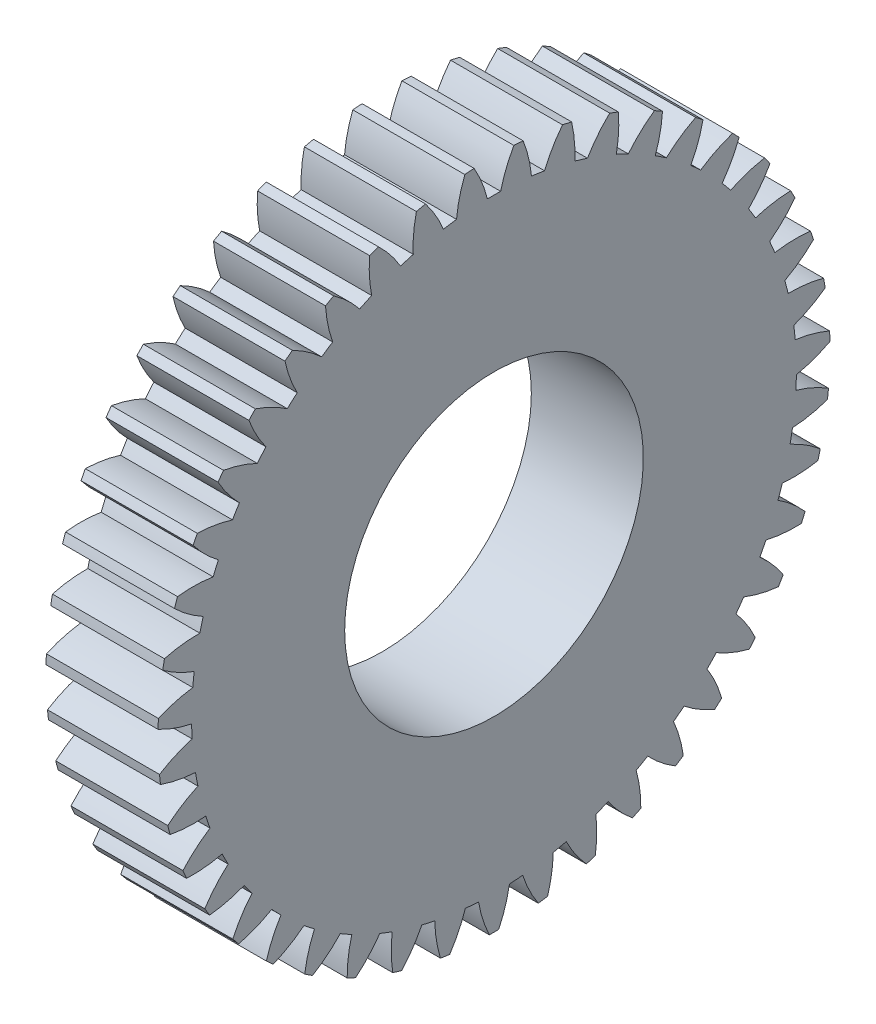
SolidWorks part; units mm, degrees
ref_plane "Plane1" through (0, 0, 0) normal (0, 0, 1) x (1, 0, 0)
ref_plane "Plane2" through (0, 0, 0) normal (0, 1, 0) x (1, 0, 0)
ref_plane "Plane3" through (0, 0, 0) normal (1, 0, 0) x (0, 0, -1)
sketch "HoldingSke" plane through (0, 0, 0) normal (0, 1, 0) x (1, 0, 0)
  line L0 (0, 0) -> (1.8284, -1.705)
  line L1 (-15, 0) -> (100, 0) construction
  line L2 (0, 0) -> (-2.1039, 2.3779)
  line L3 (0, 0) -> (-11.863, 4.5341)
  line L4 (0, 0) -> (6.316, 5.8897)
  line L5 (0, 0) -> (-46.8476, -17.4728)
  line L6 (0, 0) -> (-2.4869, -1.6779)
  line L7 (-2.1039, 2.3779) -> (8.6586, 51.2059)
  line L8 (-76.2, 54.61) -> (-74.8, 54.61)
  line L9 (-71.009, 38.7566) -> (-53.1078, 45.2721)
  line L10 (-76.2, 71.12) -> (104.1128, 71.12)
  line L11 (0, 0) -> (-3, 0)
  line L12 (-76.2, 101.6) -> (-76.185, 101.6)
  line L13 (24.9733, 27.94) -> (52.9518, 28.4284)
  line L14 (24.9733, 27.94) -> (24.9743, 27.94)
  line L15 (24.9733, 27.94) -> (100.4006, 29.5858)
  line L16 (-63.627, -0.4) -> (-12.827, -0.4)
  circle A0 centre (0, 0) radius 4
  circle A1 centre (0, 0) radius 8.099
  circle A2 centre (0, 0) radius 37.5
  circle A3 centre (0, 0) radius 4
  dimension "MHD" = 16.198
  dimension "Hub_dia" = 75
  dimension "Bore" = 8
  dimension "MBD" = 8
  dimension "Num_teeth" = 43
  dimension "Pitch" = 2.5
  dimension "Overall_len" = 50
  dimension "Show_teeth" = 43
  dimension "Thickness" = 3
  dimension "OAL" = 50.0001
  dimension "T_dim" = 1.4
  dimension "Ap" = 20
  dimension "H" = 19.05
  dimension "Pitch_radius" = 180.3128
  dimension "Width" = 3
  dimension "Backlash" = 0.015
  dimension "Addendum_fac" = 1
  dimension "Dedendum_fac" = 1.25
  dimension "Clearance_fac" = 0.25
  dimension "Dedendum_add" = 0.001
  dimension "Module" = 0.4
sketch "BasProSke" plane through (0, 0, 0) normal (0, 1, 0) x (1, 0, 0)
  line L0 (-10, 0) -> (60, 0) construction
  line L1 (0, 0) -> (0, 9)
  line L2 (0, 0) -> (3, 0)
  line L3 (3, 0) -> (3, 9)
  line L4 (3, 9) -> (0, 9)
  dimension "Thickness" = 3
  dimension "Diameter" = 18
revolve "Base-Revolve" add sketch "BasProSke" angle 360 about L0
sketch "TooCutSke" plane through (0, 0, 0) normal (1, 0, 0) x (0, 0, -1)
  line L1 (0, 0) -> (0, 107) construction
  line L2 (0, 0) -> (-0.3403, 8.5933) construction
  line L3 (0, 0) -> (-1.2548, 17.1445) construction
  line L4 (-0.3403, 8.5933) -> (-0.6274, 8.5723) construction
  arc A0 (0.1775, 8.0971) -> (-0.1775, 8.0971) centre (0, 0) ccw
  arc A1 (0.5465, 9.0088) -> (-0.5465, 9.0088) centre (0, 0) ccw
  circle A2 centre (0, 0) radius 8.6 construction
  circle A3 centre (0, 0) radius 8.0814 construction
  arc A4 (-0.1775, 8.0971) -> (-0.5465, 9.0088) centre (-3.5179, 7.2755) ccw
  arc A5 (0.5465, 9.0088) -> (0.1775, 8.0971) centre (3.5179, 7.2755) ccw
  dimension "Root_dia" = 16.198
  dimension "Overcut_dia" = 18.0508
  dimension "Pitch_dia" = 17.2
  dimension "Base_dia" = 16.1627
  dimension "Flank_rad" = 3.44
  dimension "Half_ang" = 4.186
  dimension "Half_CT" = 0.2878
extrude "ToothCut" cut sketch "TooCutSke" along normal through all
fillet "Breaks" [suppressed] radius 0.008
fillet "RootFillets" [suppressed] radius 0.101
pattern_circular "TeethCuts" count 43 every 8.372 about axis through (-10, 0, 0) along (1, 0, 0) of "ToothCut", "RootFillets", "Breaks"
sketch "HubNeaOneSke" plane through (0, 0, 0) normal (-1, 0, 0) x (0, 0, 1)
  circle A0 centre (0, 0) radius 8.099
  dimension "Diameter" = 16.198
extrude "HubNearOne" [suppressed] add sketch "HubNeaOneSke" along normal blind 47.0001
sketch "HubNeaBotSke" plane through (0, 0, 0) normal (-1, 0, 0) x (0, 0, 1)
  circle A0 centre (0, 0) radius 8.099
  dimension "Diameter" = 16.198
extrude "HubNearBoth" [suppressed] add sketch "HubNeaBotSke" along normal blind 23.5
ref_plane "FarPln" through (3, 0, 0) normal (1, 0, 0) x (0, 0, -1)
sketch "HubFarSke" plane through (3, 0, 0) normal (1, 0, 0) x (0, 0, -1)
  circle A0 centre (0, 0) radius 8.099
  dimension "Diameter" = 16.198
extrude "HubFar" [suppressed] add sketch "HubFarSke" along normal blind 23.5
sketch "BorSke" plane through (0, 0, 0) normal (1, 0, 0) x (0, 0, -1)
  circle A0 centre (0, 0) radius 4
  dimension "Diameter" = 8
extrude "Bore" cut sketch "BorSke" along normal mid plane 100.0001
sketch "KeySke" plane through (0, 0, 0) normal (1, 0, 0) x (0, 0, -1)
  line L0 (-1.5, 0) -> (-1.5, 5.4)
  line L1 (-1.5, 5.4) -> (1.5, 5.4)
  line L2 (1.5, 5.4) -> (1.5, 0)
  line L3 (0, 0) -> (0, 34) construction
  line L4 (-1.5, 0) -> (1.5, 0)
  dimension "Width" = 3
  dimension "Offset" = 5.4
extrude "Keyway" [suppressed] cut sketch "KeySke" along normal mid plane 100.0001
pattern_circular "Keyway2" [suppressed] count 2 every 90 about axis through (-10, 0, 0) along (1, 0, 0)
equation "' \"Module@HoldingSke\" = 6.35"
equation "' \"Num_teeth@HoldingSke\" = 12"
equation "' \"Ap@HoldingSke\" =  20"
equation "' \"Ap@HoldingSke\" = 20"
equation "' \"Width@HoldingSke\" = 0.5 * 25.4"
equation "' \"Hub_dia@HoldingSke\"= 1 * 25.4"
equation "' \"Hub_dia@HoldingSke\" = 1 * 25.4"
equation "' \"Overall_len@HoldingSke\" = 1.0 * 25.4"
equation "' \"Bore@HoldingSke\" = 0.75 * 25.4"
equation "' \"T_dim@HoldingSke\" = 0.1 * 25.4"
equation "' \"Width@KeySke\" = 0.25 * 25.4"
equation "' \"Show_teeth@HoldingSke\" = 13"
equation "' \"Backlash@HoldingSke\" = 0.009 * 25.4"
equation "' \"Addendum_fac@HoldingSke\" = 1.0"
equation "' \"Dedendum_fac@HoldingSke\" = 1.25"
equation "' \"Dedendum_add@HoldingSke\" = 0.00005 * 25.4"
equation "' \"Clearance_fac@HoldingSke\" = 0.25"
equation "\"Pitch@HoldingSke\" = 1 / \"Module@HoldingSke\""
equation "\"Overcut_dia@TooCutSke\" = (\"Num_teeth@HoldingSke\" + 2 * \"Addendum_fac@HoldingSke\") / \"Pitch@HoldingSke\" + 0.002 * 25.4"
equation "\"Pitch_dia@TooCutSke\" = \"Num_teeth@HoldingSke\" / \"Pitch@HoldingSke\""
equation "\"Base_dia@TooCutSke\" = \"Num_teeth@HoldingSke\" / \"Pitch@HoldingSke\" * cos((\"Ap@HoldingSke\"  * 3.14159265 / 180))"
equation "\"Root_dia@TooCutSke\" = (\"Num_teeth@HoldingSke\" + 2) / \"Pitch@HoldingSke\" - 2 * (\"Addendum_fac@HoldingSke\" + \"Dedendum_fac@HoldingSke\") / \"Pitch@HoldingSke\" - \"Dedendum_add@HoldingSke\" * 2"
equation "\"Half_ang@TooCutSke\" = 180 / \"Num_teeth@HoldingSke\""
equation "\"Half_CT@TooCutSke\" = \"Num_teeth@HoldingSke\" / \"Pitch@HoldingSke\" * sin((3.14159265 / 2 / \"Num_teeth@HoldingSke\")) / 2 - 7 * \"Backlash@HoldingSke\" / 4"
equation "\"Flank_rad@TooCutSke\" = \"Num_teeth@HoldingSke\" / \"Pitch@HoldingSke\" / 5"
equation "\"Radius@RootFillets\" = \"Clearance_fac@HoldingSke\" / \"Pitch@HoldingSke\" + \"Dedendum_add@HoldingSke\""
equation "\"Break_rad@Breaks\" = 0.02 / \"Pitch@HoldingSke\""
equation "\"Thickness@HoldingSke\" = \"Width@HoldingSke\""
equation "\"OAL@HoldingSke\" = \"Thickness@HoldingSke\""
equation "\"MHD@HoldingSke\" = (\"Num_teeth@HoldingSke\" + 2) / \"Pitch@HoldingSke\" - 2 * (\"Addendum_fac@HoldingSke\" + \"Dedendum_fac@HoldingSke\")  / \"Pitch@HoldingSke\" - \"Dedendum_add@HoldingSke\" * 2"
equation "\"MBD@HoldingSke\" = (\"Num_teeth@HoldingSke\" + 2) / \"Pitch@HoldingSke\" - 2 * (\"Addendum_fac@HoldingSke\" + \"Dedendum_fac@HoldingSke\")  / \"Pitch@HoldingSke\" - \"Dedendum_add@HoldingSke\" * 2 - 0.002 * 25.4"
equation "\"MHD@HoldingSke\" = ((sgn( \"MHD@HoldingSke\" - \"Hub_dia@HoldingSke\" )-1)*( \"MHD@HoldingSke\" - \"Hub_dia@HoldingSke\" ))/-2+ \"Hub_dia@HoldingSke\""
equation "\"MBD@HoldingSke\" = ((sgn( \"MBD@HoldingSke\" - \"Bore@HoldingSke\" )-1)*( \"MBD@HoldingSke\" - \"Bore@HoldingSke\" ))/-2+ \"Bore@HoldingSke\""
equation "\"OAL@HoldingSke\" = ((sgn( \"OAL@HoldingSke\" - \"Overall_len@HoldingSke\" )+1)*( \"OAL@HoldingSke\" - \"Overall_len@HoldingSke\" ))/2 + \"Overall_len@HoldingSke\" + 0.000002 * 25.4"
equation "\"Num_teeth@TeethCuts\" = int( \"Show_teeth@HoldingSke\" ) + 1"
equation "\"Num_teeth@TeethCuts\" = ((sgn( \"Num_teeth@TeethCuts\" - \"Num_teeth@HoldingSke\" )-1)*( \"Num_teeth@TeethCuts\" - \"Num_teeth@HoldingSke\" ))/-2+ \"Num_teeth@HoldingSke\""
equation "\"Num_teeth@TeethCuts\" = ((sgn( \"Num_teeth@TeethCuts\" - 2.0)+1)*( \"Num_teeth@TeethCuts\" - 2.0))/2 +2.0"
equation "\"Angle@TeethCuts\" = 360.0 / \"Num_teeth@HoldingSke\""
equation "\"Diameter@BasProSke\" = (\"Num_teeth@HoldingSke\" + 2 * \"Addendum_fac@HoldingSke\") / \"Pitch@HoldingSke\""
equation "\"Thickness@BasProSke\"  = \"Thickness@HoldingSke\""
equation "' \"Fillet_rad@BasProSke\" =  \"Thickness@HoldingSke\" * 0.05"
equation "' \"Fillet_rad@BasProSke\" = \"Thickness@HoldingSke\" * 0.05"
equation "\"MHD@HoldingSke\" = ((sgn( \"MHD@HoldingSke\" - \"Root_dia@TooCutSke\" )-1)*( \"MHD@HoldingSke\" - \"Root_dia@TooCutSke\" ))/-2+ \"Root_dia@TooCutSke\""
equation "\"Diameter@HubNeaOneSke\" = \"MHD@HoldingSke\""
equation "\"Length@HubNearOne\" = \"OAL@HoldingSke\" - \"Thickness@BasProSke\""
equation "\"Diameter@HubNeaBotSke\" = \"MHD@HoldingSke\""
equation "\"Length@HubNearBoth\" = ( \"OAL@HoldingSke\" - \"Thickness@BasProSke\" ) / 2.0"
equation "\"Thickness@FarPln\" = \"Thickness@BasProSke\""
equation "\"Diameter@HubFarSke\" = \"MHD@HoldingSke\""
equation "\"Length@HubFar\" = ( \"OAL@HoldingSke\" - \"Thickness@BasProSke\" ) / 2.0"
equation "\"Diameter@BorSke\" = \"MBD@HoldingSke\""
equation "\"D1@Bore\" = \"OAL@HoldingSke\" * 2.0"
equation "\"D1@Keyway\" = \"OAL@HoldingSke\" * 2.0"
equation "\"Offset@KeySke\" = \"T_dim@HoldingSke\" + \"MBD@HoldingSke\" / 2.0"
